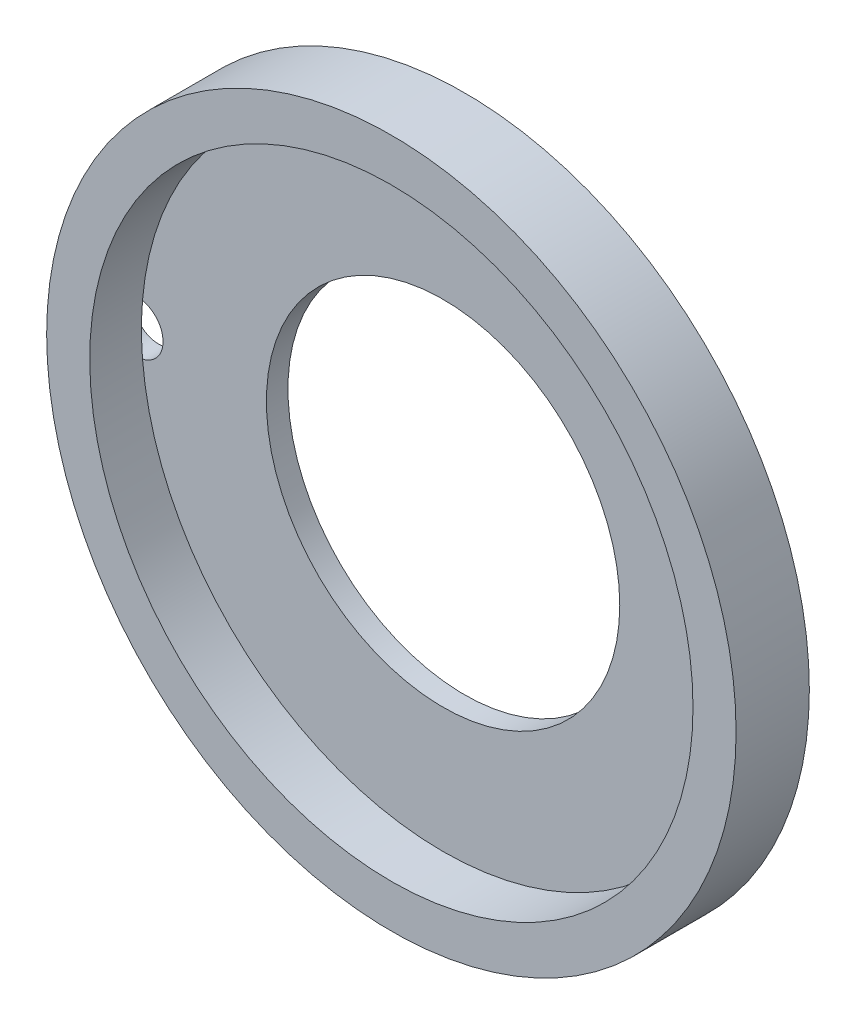
SolidWorks part; units mm, degrees
material "7075-T6 (SN)"
ref_plane "Front Plane" through (0, 0, 0) normal (0, 0, 1) x (1, 0, 0)
ref_plane "Top Plane" through (0, 0, 0) normal (0, 1, 0) x (1, 0, 0)
ref_plane "Right Plane" through (0, 0, 0) normal (1, 0, 0) x (0, 0, -1)
sketch "Sketch1" plane through (0, 0, 0) normal (0, 0, 1) x (1, 0, 0)
  circle A0 centre (0, 0) radius 8
  circle A1 centre (0, 0) radius 4.1
extrude "Outer_Flange_Contact_Annulus_ID8p2" add sketch "Sketch1" along normal blind 0.5 from offset 3
sketch "Sketch2" plane through (0, 0, 0) normal (0, 0, 1) x (1, 0, 0)
  circle A0 centre (0, 0) radius 8
  circle A1 centre (0, 0) radius 7
extrude "M14x0p5_Internal_Thread_Envelope" add sketch "Sketch2" along normal blind 1.2 from offset 2.5
sketch "Sketch3" plane through (0, 0, -3) normal (0, 0, -1) x (-1, 0, 0)
  circle A0 centre (7.1, 0) radius 0.6
  circle A1 centre (-7.1, 0) radius 0.6
extrude "Two_Pin_Wrench_Holes_D1p2" cut sketch "Sketch3" against normal blind 0.5001
